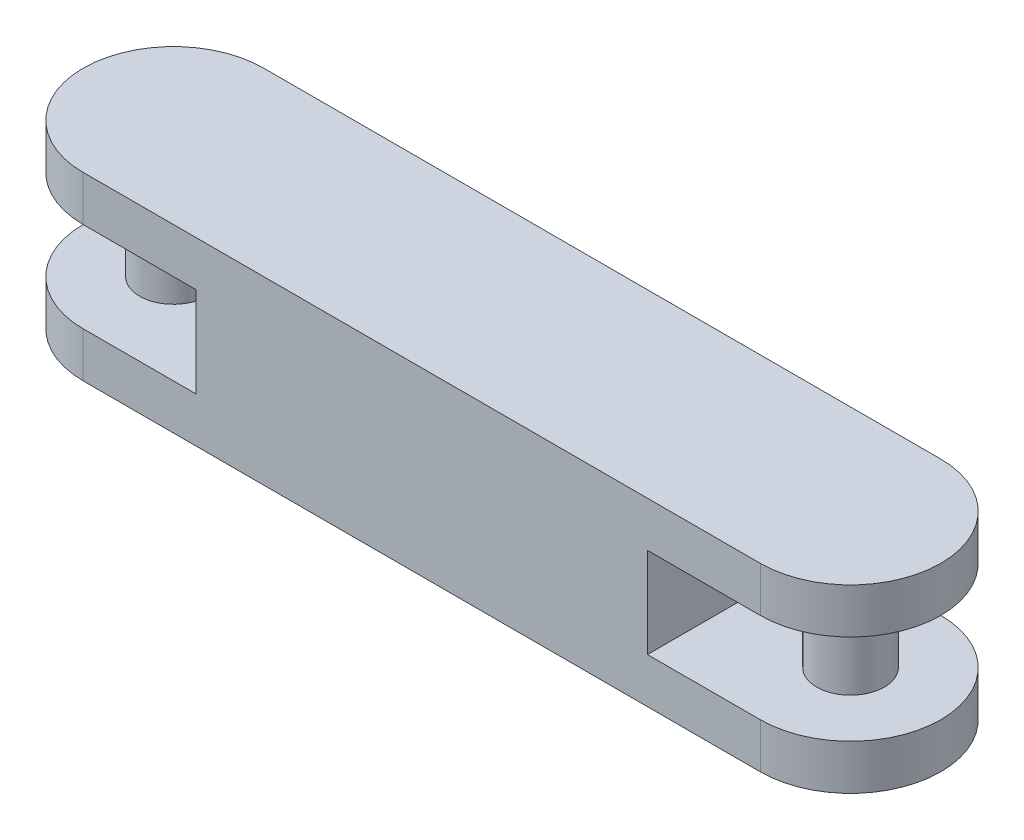
SolidWorks part; units mm, degrees
ref_plane "Front Plane" through (0, 0, 0) normal (0, 0, 1) x (1, 0, 0)
ref_plane "Top Plane" through (0, 0, 0) normal (0, 1, 0) x (1, 0, 0)
ref_plane "Right Plane" through (0, 0, 0) normal (1, 0, 0) x (0, 0, -1)
sketch "Sketch2" plane through (0, 0, 0) normal (0, 1, 0) x (1, 0, 0)
  line L0 (0, 0) -> (300, 0) construction
  line L1 (0, 40) -> (300, 40)
  line L2 (0, -40) -> (300, -40)
  arc A0 (0, 40) -> (0, -40) centre (0, 0) ccw
  arc A1 (300, -40) -> (300, 40) centre (300, 0) ccw
  point P3 (150, 0)
  dimension "D1" = 300
  dimension "D2" = 80
extrude "Boss-Extrude1" add sketch "Sketch2" along normal mid plane 80
sketch "Sketch3" plane through (0, 0, 40) normal (0, 0, 1) x (1, 0, 0)
  line L0 (-40, 0) -> (50, 0)
  line L1 (-40, 40) -> (-40, -40) construction
  line L2 (340, 0) -> (250, 0)
  line L3 (340, -40) -> (340, 40) construction
  dimension "D1" = 90
extrude "Cut-Extrude-Thin1" cut sketch "Sketch3" against normal blind 80 thin thin type mid plane wall 40
sketch "Sketch4" plane through (0, -40, 0) normal (0, -1, 0) x (1, 0, 0)
  circle A0 centre (0, 0) radius 15
  circle A1 centre (300, 0) radius 15
  dimension "D1" = 30
extrude "Boss-Extrude2" add sketch "Sketch4" against normal up to surface (80 mm away) up to face at (150, 40, 0)
